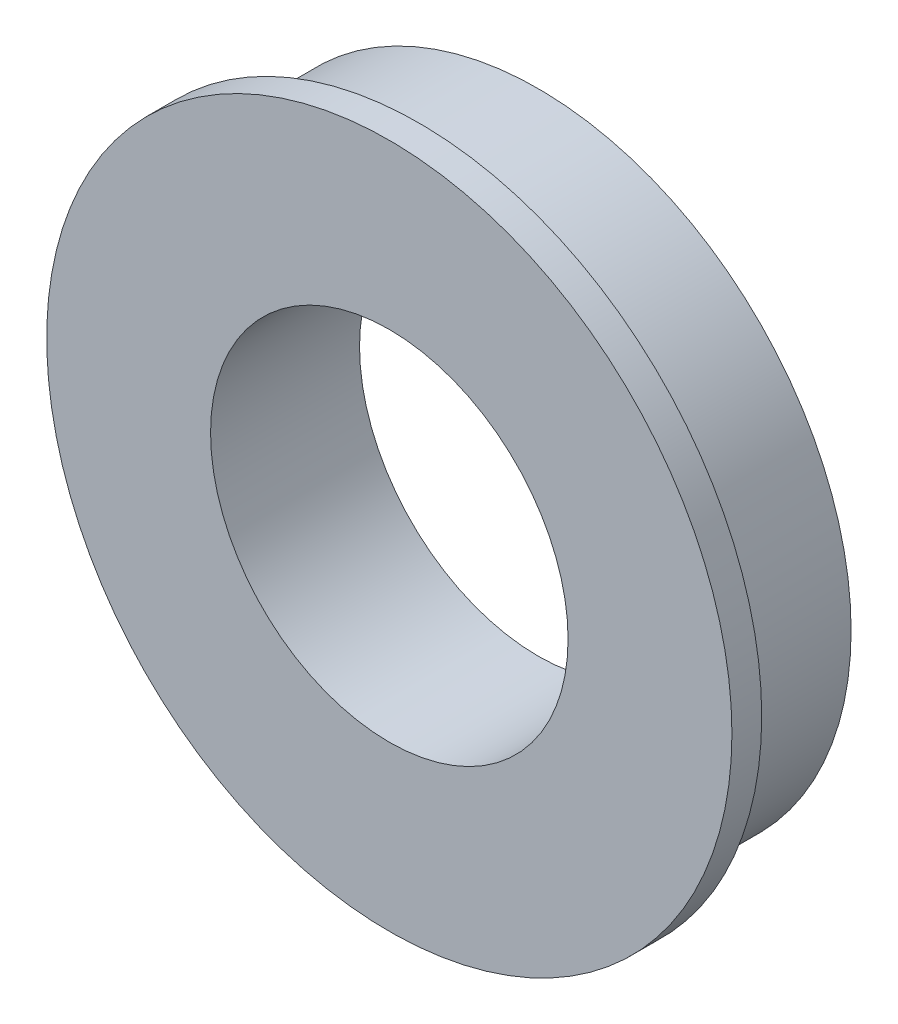
SolidWorks part; units mm, degrees
material "黄铜"
ref_plane "前视基准面" through (0, 0, 0) normal (0, 0, 1) x (1, 0, 0)
ref_plane "上视基准面" through (0, 0, 0) normal (0, 1, 0) x (1, 0, 0)
ref_plane "右视基准面" through (0, 0, 0) normal (1, 0, 0) x (0, 0, -1)
sketch "草图1" plane through (0, 0, 0) normal (0, 0, 1) x (1, 0, 0)
  circle A0 centre (0, 0) radius 6
  circle A1 centre (0, 0) radius 10.5
  dimension "D1" = 12
  dimension "D2" = 21
extrude "凸台-拉伸1" add sketch "草图1" along normal blind 4
sketch "草图2" plane through (0, 0, 4) normal (0, 0, 1) x (1, 0, 0)
  circle A0 centre (0, 0) radius 6
  circle A1 centre (0, 0) radius 11.5
  dimension "D1" = 23
extrude "凸台-拉伸2" add sketch "草图2" along normal blind 1
